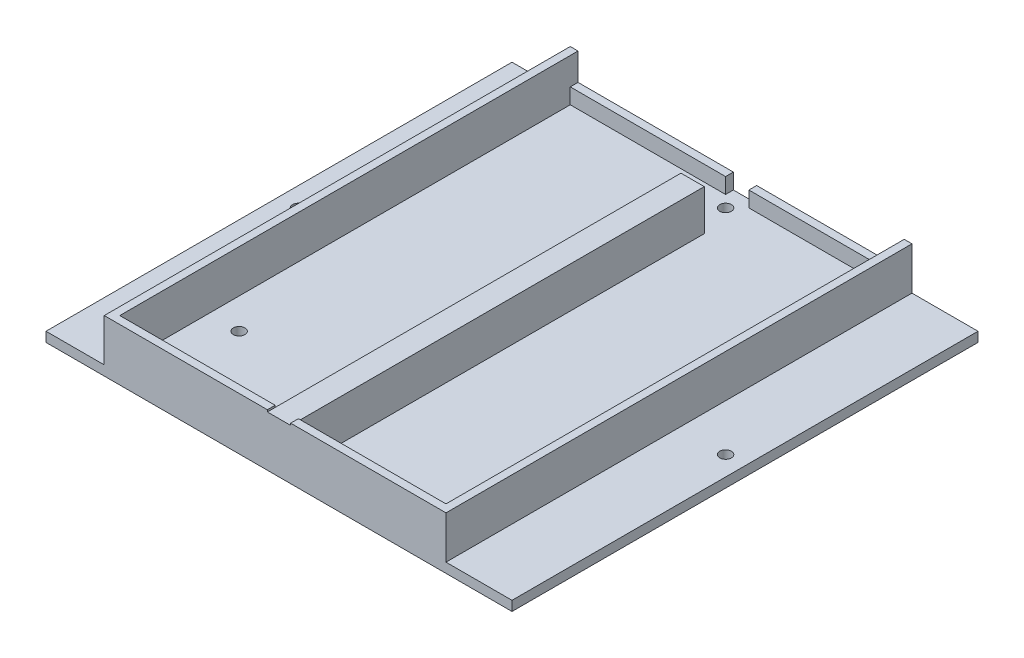
SolidWorks part; units mm, degrees
ref_plane "Front Plane" through (0, 0, 0) normal (0, 0, 1) x (1, 0, 0)
ref_plane "Top Plane" through (0, 0, 0) normal (0, 1, 0) x (1, 0, 0)
ref_plane "Right Plane" through (0, 0, 0) normal (1, 0, 0) x (0, 0, -1)
sketch "Sketch1" plane through (0, 0, 0) normal (0, 1, 0) x (1, 0, 0)
  line L4 (0, -60) -> (0, -40)
  line L5 (0, -40) -> (-44.7214, -40)
  line L6 (-44.7214, -40) -> (44.7214, -40)
  line L7 (0, -60) -> (0, -50)
  line L8 (0, -50) -> (-33.1662, -50)
  line L9 (-33.1662, -50) -> (33.1662, -50)
  circle A2 centre (0, 0) radius 60
  spline S0 degree 3 poles (-44.7214, -40) (-33.6128, -52.6793) (-0.0838, -67.3518) (33.7217, -52.6172) (44.7214, -40) knots 0 0 0 0 0.500218 1 1 1 1
  spline S1 degree 2 poles (-33.1662, -50) (-18.0093, -59.9054) (0, -60) knots 0 0 0 1 1 1
  spline S2 degree 2 poles (0, -60) (18.0084, -59.9056) (33.1662, -50) knots 0 0 0 1 1 1
extrude "Boss-Extrude3" add sketch "Sketch1" along normal blind 2.5 contours L6 A2 L5 | L5 A2 L8 L4 | L9 A2 L6 L4 | L4 S2 S0 L9 | L8 S1 S0 L4
sketch "Sketch3" plane through (0, 2.5, 0) normal (0, 1, 0) x (1, 0, 0)
  line L0 (0, 60) -> (-60, 60)
  line L1 (-60, 60) -> (-60, -60)
  line L2 (-60, -60) -> (60, -60)
  line L3 (60, -60) -> (60, 60)
  line L4 (60, 60) -> (0, 60)
  arc A1 (33.1662, -50) -> (-33.1662, -50) centre (0, 0) ccw construction
extrude "Boss-Extrude4" add sketch "Sketch3" against normal blind 2.5
sketch "Sketch4" plane through (0, 2.5, 0) normal (0, 1, 0) x (1, 0, 0)
  line L0 (0, 60) -> (-3, 60)
  line L2 (60, 60) -> (-60, 60) construction
  line L3 (-3, 60) -> (3, 60)
  line L5 (3, 60) -> (3, -60)
  line L6 (-60, -60) -> (60, -60) construction
  line L7 (3, -60) -> (-3, -60)
  line L8 (-3, -60) -> (-3, 60)
  line M3 (60, 60) -> (-60, 60)
  line M5 (-60, -60) -> (60, -60)
extrude "Boss-Extrude5" add sketch "Sketch4" along normal blind 10.5 contours L8 L5 M5 M3
sketch "Sketch5" plane through (0, 2.5, 0) normal (0, 1, 0) x (1, 0, 0)
  line L0 (-3, -60) -> (-43, -60)
  line L1 (-60, -60) -> (-3, -60) construction
  line L3 (-3, 60) -> (-60, 60) construction
  line L4 (-43, 60) -> (-45, 60)
  line L5 (-45, 60) -> (-45, -60)
  line L6 (-45, -60) -> (-45, -58)
  line L8 (-3, -60) -> (-3, 60) construction
  line L9 (-3, -58) -> (-3, -60)
  line L10 (-43, -60) -> (-45, -60)
  line L11 (-43, -58) -> (-43, 60)
  line L12 (-45, -60) -> (-3, -60)
  line L13 (-3, -58) -> (-43, -58)
  line M8 (-60, -60) -> (-3, -60)
  line M9 (-3, -60) -> (-3, 60)
  line M10 (-3, 60) -> (-60, 60)
extrude "Boss-Extrude8" add sketch "Sketch5" along normal blind 11 contours L13 L11 L5 M9 M10 M8
sketch "Sketch7" plane through (0, 2.5, 0) normal (0, 1, 0) x (1, 0, 0)
  line L0 (3, -60) -> (43, -60)
  line L1 (3, -60) -> (60, -60) construction
  line L2 (43, -60) -> (43, 60)
  line L3 (60, 60) -> (3, 60) construction
  line L4 (43, 60) -> (41, 60)
  line L5 (41, 60) -> (41, -58)
  line L6 (41, -58) -> (3, -58)
  line L7 (3, 60) -> (3, -60) construction
  line L8 (3, -58) -> (3, -60)
extrude "Boss-Extrude9" add sketch "Sketch7" along normal blind 11
sketch "Sketch8" plane through (0, 2.5, 0) normal (0, 1, 0) x (1, 0, 0)
  line L0 (-43, 60) -> (-43, 58)
  line L1 (-43, -58) -> (-43, 60) construction
  line L2 (-43, 58) -> (41, 58)
  line L3 (41, 60) -> (41, -58) construction
  line L4 (41, 58) -> (41, 60)
  line L5 (41, 60) -> (-43, 60)
extrude "Boss-Extrude11" add sketch "Sketch8" along normal blind 4
sketch "Sketch9" plane through (0, 2.5, 0) normal (0, 1, 0) x (1, 0, 0)
  line L0 (0, 0) -> (55, 0)
  line L1 (-3, -58) -> (-3, 58) construction
  line L2 (3, 60) -> (-3, 60)
  line L3 (3, 60) -> (3, 52.9463)
  line L4 (3, 52.9463) -> (-3, 52.9463)
  line L5 (-3, 60) -> (-3, 52.9463)
extrude "Cut-Extrude1" cut sketch "Sketch9" along normal blind 28 contours L2 L5 L4 L3
sketch "Sketch10" plane through (0, 2.5, 0) normal (0, 1, 0) x (1, 0, 0)
  line L0 (0, 0) -> (0, 55)
  line L1 (3, 52.9463) -> (3, -58) construction
  line L2 (-3, 52.9463) -> (3, 52.9463)
  line L3 (-3, 52.9463) -> (-3, 46.5076)
  line L4 (-3, 46.5076) -> (3, 46.5076)
  line L5 (3, 52.9463) -> (3, 46.5076)
extrude "Cut-Extrude4" cut sketch "Sketch10" along normal blind 11 contours L3 L4 L5 L2
sketch "Sketch11" plane through (0, 2.5, 0) normal (0, 1, 0) x (1, 0, 0)
  line L0 (0, 0) -> (-35.1291, -35.1291)
  line L1 (0, 0) -> (35.1291, -35.1291)
  circle A0 centre (-35.1291, -35.1291) radius 1.5
  circle A1 centre (35.1291, -35.1291) radius 1.5
extrude "Cut-Extrude5" cut sketch "Sketch11" against normal blind 14 contours A0 | A1
sketch "Sketch13" plane through (0, 13, 0) normal (0, 1, 0) x (1, 0, 0)
  line L0 (0, 0) -> (-55, 0)
  line L1 (0, 0) -> (55, 0)
  circle A0 centre (-55, 0) radius 1.5
  circle A1 centre (55, 0) radius 1.5
extrude "Cut-Extrude6" cut sketch "Sketch13" against normal blind 14
sketch "Sketch15" plane through (0, 2.5, 0) normal (0, 1, 0) x (1, 0, 0)
  line L0 (0, 0) -> (0, 55)
  circle A0 centre (0, 55) radius 1.5
extrude "Cut-Extrude7" cut sketch "Sketch15" against normal blind 14
